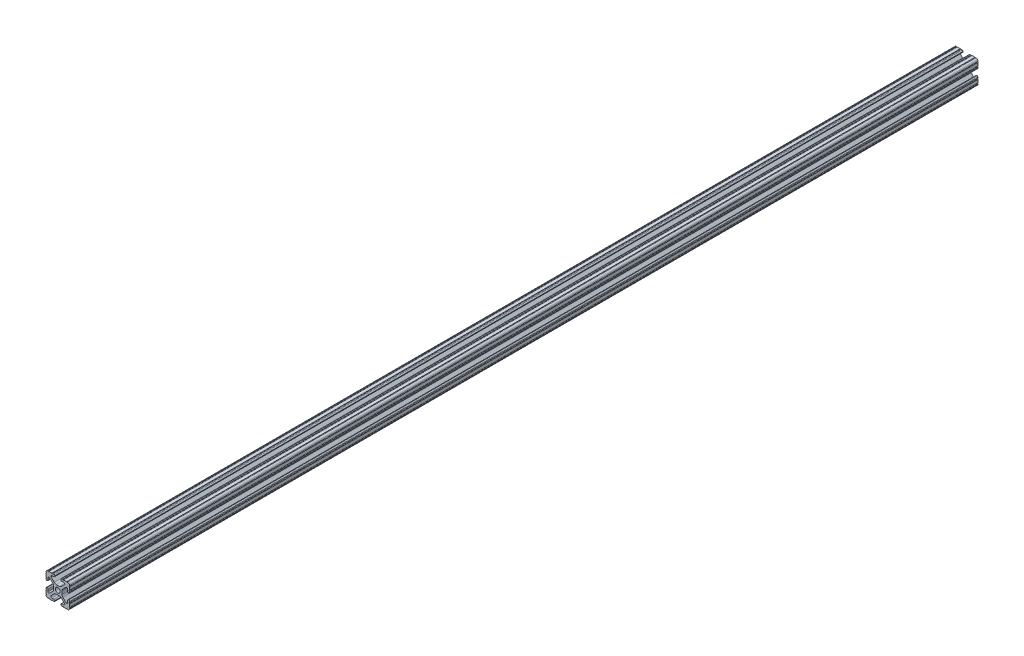
SolidWorks part; units mm, degrees
material "6061 Alloy"
ref_plane "Front Plane" through (0, 0, 0) normal (0, 0, 1) x (1, 0, 0)
ref_plane "Top Plane" through (0, 0, 0) normal (0, 1, 0) x (1, 0, 0)
ref_plane "Right Plane" through (0, 0, 0) normal (1, 0, 0) x (0, 0, -1)
sketch "Sketch1" plane through (0, 0, 0) normal (0, 0, 1) x (1, 0, 0)
  line L0 (-7.1797, -8.6452) -> (-3.9523, -5.4237)
  line L1 (-1.7093, -4.4958) -> (1.7093, -4.4958)
  line L2 (3.9523, -5.4237) -> (7.1797, -8.6452)
  line L3 (6.4164, -10.4902) -> (4.2875, -10.4902)
  line L4 (3.2385, -11.5392) -> (3.2385, -11.651)
  line L5 (4.2875, -12.7) -> (5.3171, -12.7)
  line L6 (6.3331, -12.7) -> (9.5504, -12.7)
  line L7 (12.7, -9.5504) -> (12.7, -6.3331)
  line L8 (12.7, -5.3171) -> (12.7, -4.2875)
  line L9 (11.651, -3.2385) -> (11.5392, -3.2385)
  line L10 (10.4902, -4.2875) -> (10.4902, -6.4021)
  line L11 (8.7371, -7.1294) -> (5.441, -3.8408)
  line L12 (4.5085, -1.5932) -> (4.5085, 1.5932)
  line L13 (5.441, 3.8408) -> (8.7371, 7.1294)
  line L14 (10.4902, 6.4021) -> (10.4902, 4.2875)
  line L15 (11.5392, 3.2385) -> (11.651, 3.2385)
  line L16 (12.7, 4.2875) -> (12.7, 5.3171)
  line L17 (12.7, 6.3331) -> (12.7, 9.5504)
  line L18 (9.5504, 12.7) -> (6.3331, 12.7)
  line L19 (5.3171, 12.7) -> (4.2875, 12.7)
  line L20 (3.2385, 11.651) -> (3.2385, 11.5392)
  line L21 (4.2875, 10.4902) -> (6.4768, 10.4902)
  line L22 (7.207, 8.7244) -> (3.8983, 5.4232)
  line L23 (1.6558, 4.4958) -> (-1.6558, 4.4958)
  line L24 (-3.8983, 5.4232) -> (-7.207, 8.7244)
  line L25 (-6.4768, 10.4902) -> (-4.2875, 10.4902)
  line L26 (-3.2385, 11.5392) -> (-3.2385, 11.651)
  line L27 (-4.2875, 12.7) -> (-5.3171, 12.7)
  line L28 (-6.3331, 12.7) -> (-9.5504, 12.7)
  line L29 (-12.7, 9.5504) -> (-12.7, 6.3331)
  line L30 (-12.7, 5.3171) -> (-12.7, 4.2875)
  line L31 (-11.651, 3.2385) -> (-11.5392, 3.2385)
  line L32 (-10.4902, 4.2875) -> (-10.4902, 6.4021)
  line L33 (-8.7371, 7.1294) -> (-5.441, 3.8408)
  line L34 (-4.5085, 1.5932) -> (-4.5085, -1.5932)
  line L35 (-5.441, -3.8408) -> (-8.7371, -7.1294)
  line L36 (-10.4902, -6.4021) -> (-10.4902, -4.2875)
  line L37 (-11.5392, -3.2385) -> (-11.651, -3.2385)
  line L38 (-12.7, -4.2875) -> (-12.7, -5.3171)
  line L39 (-12.7, -6.3331) -> (-12.7, -9.5504)
  line L40 (-9.5504, -12.7) -> (-6.3331, -12.7)
  line L41 (-5.3171, -12.7) -> (-4.2875, -12.7)
  line L42 (-3.2385, -11.651) -> (-3.2385, -11.5392)
  line L43 (-4.2875, -10.4902) -> (-6.4164, -10.4902)
  arc A0 (-6.4164, -10.4902) -> (-7.1797, -8.6452) centre (-6.4164, -9.4098) cw
  arc A1 (-3.9523, -5.4237) -> (-1.7093, -4.4958) centre (-1.7093, -7.6708) cw
  arc A2 (1.7093, -4.4958) -> (3.9523, -5.4237) centre (1.7093, -7.6708) cw
  arc A3 (7.1797, -8.6452) -> (6.4164, -10.4902) centre (6.4164, -9.4098) cw
  arc A4 (4.2875, -10.4902) -> (3.2385, -11.5392) centre (4.2875, -11.5392) ccw
  arc A5 (3.2385, -11.651) -> (4.2875, -12.7) centre (4.2875, -11.651) ccw
  arc A6 (5.3171, -12.7) -> (6.3331, -12.7) centre (5.8251, -12.7) cw
  arc A7 (9.5504, -12.7) -> (10.5664, -12.6998) centre (10.0584, -12.7) cw
  arc A8 (10.5664, -12.6998) -> (12.6998, -10.5664) centre (10.5918, -10.5918) ccw
  arc A9 (12.6998, -10.5664) -> (12.7, -9.5504) centre (12.7, -10.0584) cw
  arc A10 (12.7, -6.3331) -> (12.7, -5.3171) centre (12.7, -5.8251) cw
  arc A11 (12.7, -4.2875) -> (11.651, -3.2385) centre (11.651, -4.2875) ccw
  arc A12 (11.5392, -3.2385) -> (10.4902, -4.2875) centre (11.5392, -4.2875) ccw
  arc A13 (10.4902, -6.4021) -> (8.7371, -7.1294) centre (9.4628, -6.4021) cw
  arc A14 (5.441, -3.8408) -> (4.5085, -1.5932) centre (7.6835, -1.5932) cw
  arc A15 (4.5085, 1.5932) -> (5.441, 3.8408) centre (7.6835, 1.5932) cw
  arc A16 (8.7371, 7.1294) -> (10.4902, 6.4021) centre (9.4628, 6.4021) cw
  arc A17 (10.4902, 4.2875) -> (11.5392, 3.2385) centre (11.5392, 4.2875) ccw
  arc A18 (11.651, 3.2385) -> (12.7, 4.2875) centre (11.651, 4.2875) ccw
  arc A19 (12.7, 5.3171) -> (12.7, 6.3331) centre (12.7, 5.8251) cw
  arc A20 (12.7, 9.5504) -> (12.6998, 10.5664) centre (12.7, 10.0584) cw
  arc A21 (12.6998, 10.5664) -> (10.5664, 12.6998) centre (10.5918, 10.5918) ccw
  arc A22 (10.5664, 12.6998) -> (9.5504, 12.7) centre (10.0584, 12.7) cw
  arc A23 (6.3331, 12.7) -> (5.3171, 12.7) centre (5.8251, 12.7) cw
  arc A24 (4.2875, 12.7) -> (3.2385, 11.651) centre (4.2875, 11.651) ccw
  arc A25 (3.2385, 11.5392) -> (4.2875, 10.4902) centre (4.2875, 11.5392) ccw
  arc A26 (6.4768, 10.4902) -> (7.207, 8.7244) centre (6.4768, 9.4563) cw
  arc A27 (3.8983, 5.4232) -> (1.6558, 4.4958) centre (1.6558, 7.6708) cw
  arc A28 (-1.6558, 4.4958) -> (-3.8983, 5.4232) centre (-1.6558, 7.6708) cw
  arc A29 (-7.207, 8.7244) -> (-6.4768, 10.4902) centre (-6.4768, 9.4563) cw
  arc A30 (-4.2875, 10.4902) -> (-3.2385, 11.5392) centre (-4.2875, 11.5392) ccw
  arc A31 (-3.2385, 11.651) -> (-4.2875, 12.7) centre (-4.2875, 11.651) ccw
  arc A32 (-5.3171, 12.7) -> (-6.3331, 12.7) centre (-5.8251, 12.7) cw
  arc A33 (-9.5504, 12.7) -> (-10.5664, 12.6998) centre (-10.0584, 12.7) cw
  arc A34 (-10.5664, 12.6998) -> (-12.6998, 10.5664) centre (-10.5918, 10.5918) ccw
  arc A35 (-12.6998, 10.5664) -> (-12.7, 9.5504) centre (-12.7, 10.0584) cw
  arc A36 (-12.7, 6.3331) -> (-12.7, 5.3171) centre (-12.7, 5.8251) cw
  arc A37 (-12.7, 4.2875) -> (-11.651, 3.2385) centre (-11.651, 4.2875) ccw
  arc A38 (-11.5392, 3.2385) -> (-10.4902, 4.2875) centre (-11.5392, 4.2875) ccw
  arc A39 (-10.4902, 6.4021) -> (-8.7371, 7.1294) centre (-9.4628, 6.4021) cw
  arc A40 (-5.441, 3.8408) -> (-4.5085, 1.5932) centre (-7.6835, 1.5932) cw
  arc A41 (-4.5085, -1.5932) -> (-5.441, -3.8408) centre (-7.6835, -1.5932) cw
  arc A42 (-8.7371, -7.1294) -> (-10.4902, -6.4021) centre (-9.4628, -6.4021) cw
  arc A43 (-10.4902, -4.2875) -> (-11.5392, -3.2385) centre (-11.5392, -4.2875) ccw
  arc A44 (-11.651, -3.2385) -> (-12.7, -4.2875) centre (-11.651, -4.2875) ccw
  arc A45 (-12.7, -5.3171) -> (-12.7, -6.3331) centre (-12.7, -5.8251) cw
  arc A46 (-12.7, -9.5504) -> (-12.6998, -10.5664) centre (-12.7, -10.0584) cw
  arc A47 (-12.6998, -10.5664) -> (-10.5664, -12.6998) centre (-10.5918, -10.5918) ccw
  arc A48 (-10.5664, -12.6998) -> (-9.5504, -12.7) centre (-10.0584, -12.7) cw
  arc A49 (-6.3331, -12.7) -> (-5.3171, -12.7) centre (-5.8251, -12.7) cw
  arc A50 (-4.2875, -12.7) -> (-3.2385, -11.651) centre (-4.2875, -11.651) ccw
  arc A51 (-3.2385, -11.5392) -> (-4.2875, -10.4902) centre (-4.2875, -11.5392) ccw
  circle A52 centre (0, 0) radius 2.6035
extrude "Boss-Extrude1" add sketch "Sketch1" against normal blind 977.9
